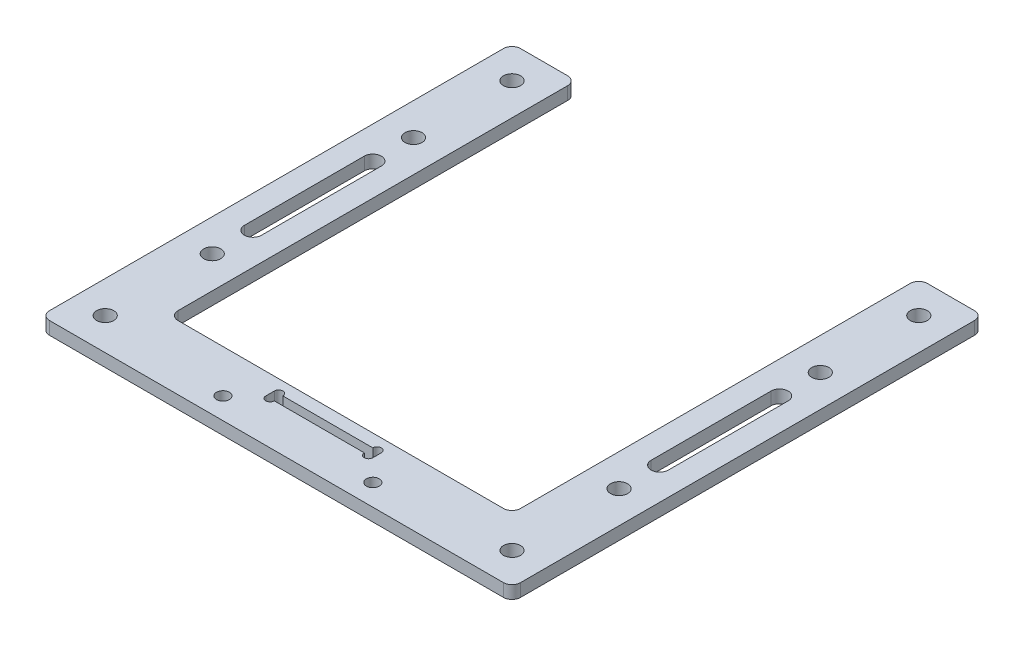
SolidWorks part; units mm, degrees
material "Thornel Mat VMA"
ref_plane "前视基准面" through (0, 0, 0) normal (0, 0, 1) x (1, 0, 0)
ref_plane "上视基准面" through (0, 0, 0) normal (0, 1, 0) x (1, 0, 0)
ref_plane "右视基准面" through (0, 0, 0) normal (1, 0, 0) x (0, 0, -1)
sketch "草图1" plane through (0, 0, 0) normal (0, 1, 0) x (1, 0, 0)
  line L0 (55, 110) -> (55, 0)
  line L2 (47.5, 0) -> (47.5, 110) construction
  line L5 (40, 15) -> (-40, 15)
  line L9 (40, 110) -> (55, 110)
  line L11 (-55, 0) -> (55, 0)
  line L15 (40, 110) -> (40, 15)
  line L21 (0, -55) -> (0, 55) construction
  line L22 (-40, 110) -> (-40, 15)
  line L24 (-55, 110) -> (-55, 0)
  line L25 (-40, 110) -> (-55, 110)
  line L26 (0, 0) -> (0, 10) construction
  line L27 (-12.5, 12) -> (12.5, 12)
  line L28 (-12.5, 12) -> (-12.5, 10)
  line L29 (-12.5, 10) -> (12.5, 10)
  line L30 (12.5, 12) -> (12.5, 10)
  circle A0 centre (47.5, 32.5) radius 2
  circle A1 centre (47.5, 7.5) radius 2
  circle A2 centre (47.5, 79.5) radius 2
  circle A4 centre (47.5, 102.5) radius 2
  circle A5 centre (-47.5, 102.5) radius 2
  circle A6 centre (-47.5, 79.5) radius 2
  circle A7 centre (-47.5, 7.5) radius 2
  circle A8 centre (-47.5, 32.5) radius 2
  circle A9 centre (17.5, 5) radius 1.5
  circle A10 centre (-17.5, 5) radius 1.5
  dimension "D4" = 7.5
  dimension "D3" = 4
  dimension "D5" = 47
  dimension "D7" = 23
  dimension "D10" = 7.5
  dimension "D13" = 3
  dimension "D14" = 5
  dimension "D15" = 5
  dimension "D1" = 25
  dimension "D2" = 15
  dimension "D6" = 110
  dimension "D8" = 15
  dimension "D9" = 2
  dimension "D11" = 10
  dimension "D12" = 25
extrude "凸台-拉伸1" add sketch "草图1" along normal blind 3
sketch "草图2" plane through (0, 3, 0) normal (0, 1, 0) x (1, 0, 0)
  line L0 (12.5, 12) -> (-12.5, 12) construction
  line L1 (-12.5, 10) -> (12.5, 10) construction
  line L2 (-12.5, 10) -> (-10.5, 10)
  line L3 (12.5, 12) -> (10.5, 12)
  line L4 (-10.5, 12) -> (-12.5, 12)
  line L5 (10.5, 10) -> (12.5, 10)
  arc A0 (-10.5, 12) -> (-12.5, 12) centre (-11.5, 12) ccw
  arc A1 (-12.5, 10) -> (-10.5, 10) centre (-11.5, 10) ccw
  arc A2 (12.5, 12) -> (10.5, 12) centre (11.5, 12) ccw
  arc A3 (10.5, 10) -> (12.5, 10) centre (11.5, 10) ccw
  dimension "D1" = 2
extrude "切除-拉伸1" cut sketch "草图2" against normal through all
sketch "草图3" plane through (0, 3, 0) normal (0, 1, 0) x (1, 0, 0)
  line L0 (-47.5, 70) -> (-47.5, 42) construction
  line L1 (-45.5, 70) -> (-45.5, 42)
  line L2 (-49.5, 70) -> (-49.5, 42)
  line L3 (-47.5, 70) -> (-47.5, 79.5) construction
  line L4 (0, -55) -> (0, 55) construction
  line L6 (47.5, 70) -> (47.5, 42) construction
  line L7 (45.5, 70) -> (45.5, 42)
  line L8 (49.5, 70) -> (49.5, 42)
  arc A0 (-45.5, 70) -> (-49.5, 70) centre (-47.5, 70) ccw
  arc A1 (-49.5, 42) -> (-45.5, 42) centre (-47.5, 42) ccw
  circle A2 centre (-47.5, 79.5) radius 2 construction
  circle A3 centre (-47.5, 32.5) radius 2 construction
  arc A4 (45.5, 70) -> (49.5, 70) centre (47.5, 70) cw
  arc A5 (49.5, 42) -> (45.5, 42) centre (47.5, 42) cw
  point P2 (-47.5, 56)
  point P10 (-47.5, 72)
  point P13 (-47.5, 40)
  point P21 (47.5, 56)
  dimension "D1" = 7.5
  dimension "D2" = 7.5
  dimension "D3" = 4
extrude "切除-拉伸2" cut sketch "草图3" against normal through all
fillet "圆角1" radius 2 8 edges at (55, 1.5, -110) (55, 1.5, 0) (40, 1.5, -15) (-40, 1.5, -15) (-55, 1.5, 0) (-55, 1.5, -110) (40, 1.5, -110) (-40, 1.5, -110)
